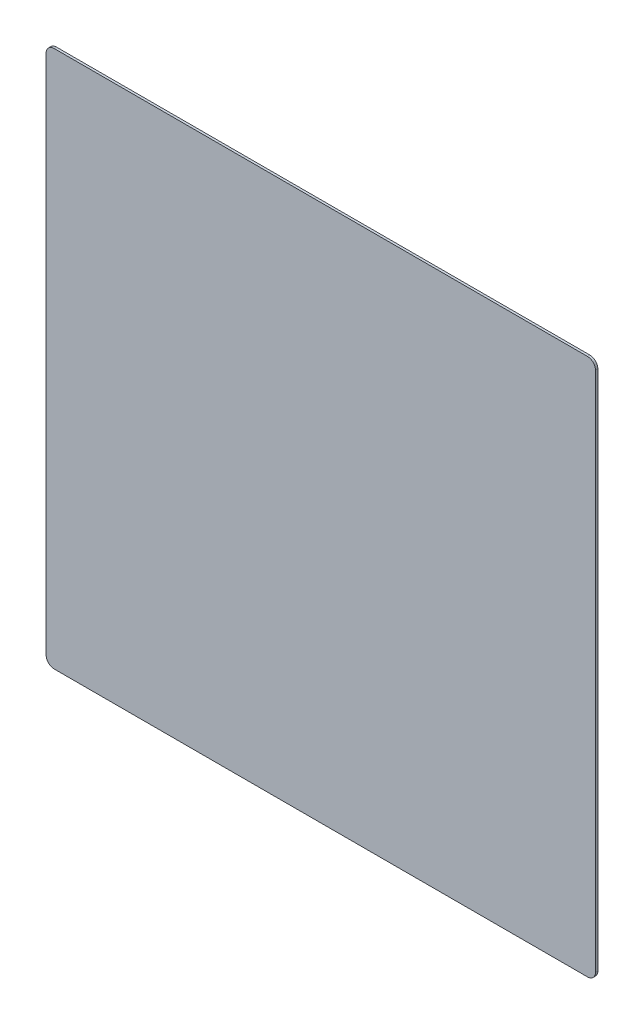
SolidWorks part; units mm, degrees
material "玻璃"
ref_plane "前视基准面" through (0, 0, 0) normal (0, 0, 1) x (1, 0, 0)
ref_plane "上视基准面" through (0, 0, 0) normal (0, 1, 0) x (1, 0, 0)
ref_plane "右视基准面" through (0, 0, 0) normal (1, 0, 0) x (0, 0, -1)
sketch "草图1" plane through (0, 0, 0) normal (0, 0, 1) x (1, 0, 0)
  line L1 (-345, -337.5) -> (345, -337.5)
  line L2 (-345, -337.5) -> (-345, 337.5)
  line L3 (-345, 337.5) -> (345, 337.5)
  line L4 (345, -337.5) -> (345, 337.5)
  line L5 (-345, -337.5) -> (345, 337.5) construction
  line L6 (-345, 337.5) -> (345, -337.5) construction
  point P0 (0, 0)
  dimension "D1" = 675
  dimension "D2" = 690
extrude "凸台-拉伸1" add sketch "草图1" along normal blind 3
fillet "圆角1" radius 10 4 edges at (-345, -337.5, 1.5) (345, -337.5, 1.5) (-345, 337.5, 1.5) (345, 337.5, 1.5)
